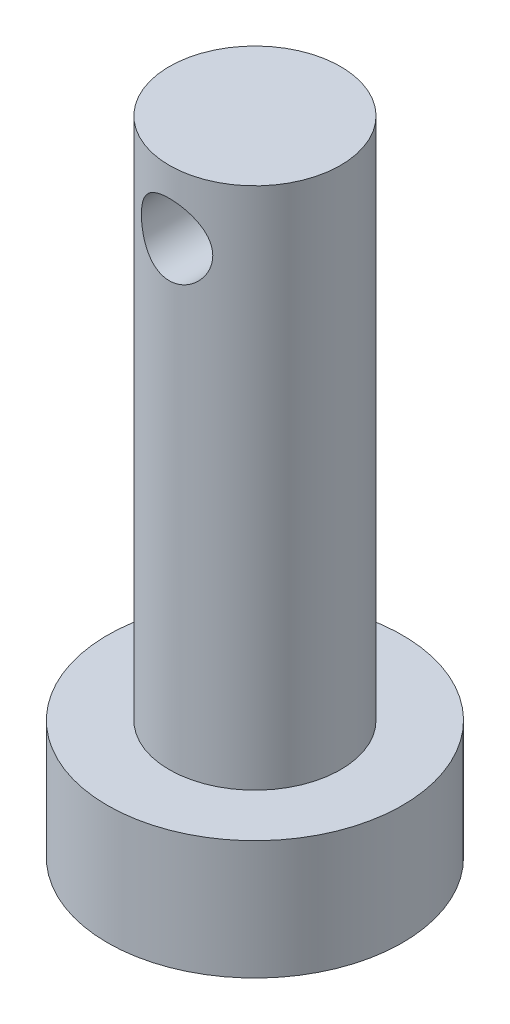
SolidWorks part; units mm, degrees
ref_plane "Front Plane" through (0, 0, 0) normal (0, 0, 1) x (1, 0, 0)
ref_plane "Top Plane" through (0, 0, 0) normal (0, 1, 0) x (1, 0, 0)
ref_plane "Right Plane" through (0, 0, 0) normal (1, 0, 0) x (0, 0, -1)
sketch "Sketch2" plane through (0, 0, 0) normal (0, 1, 0) x (1, 0, 0)
  circle A0 centre (0, 0) radius 3.1
  dimension "D1" = 6.2
extrude "Boss-Extrude1" add sketch "Sketch2" along normal blind 2.5
ref_plane "Plane1" through (0, 2.5, 0) normal (0, 1, 0) x (1, 0, 0)
sketch "Sketch3" plane through (0, 2.5, 0) normal (0, 1, 0) x (1, 0, 0)
  circle A0 centre (0, 0) radius 1.8
  dimension "D1" = 3.6
extrude "Boss-Extrude3" add sketch "Sketch3" along normal blind 11 contours A0
sketch "Sketch4" plane through (0, 0, 0) normal (0, 0, 1) x (1, 0, 0)
  line L0 (1.8, 13.5) -> (1.8, 12.15)
  line L1 (1.8, 2.5) -> (1.8, 13.5) construction
  line L2 (1.8, 12.15) -> (0.75, 12.15)
  circle A0 centre (0, 12.15) radius 0.75
  dimension "D2" = 1.5
  dimension "D1" = 1.35
extrude "Cut-Extrude1" cut sketch "Sketch4" against normal through all both and the other way through all contours A0
